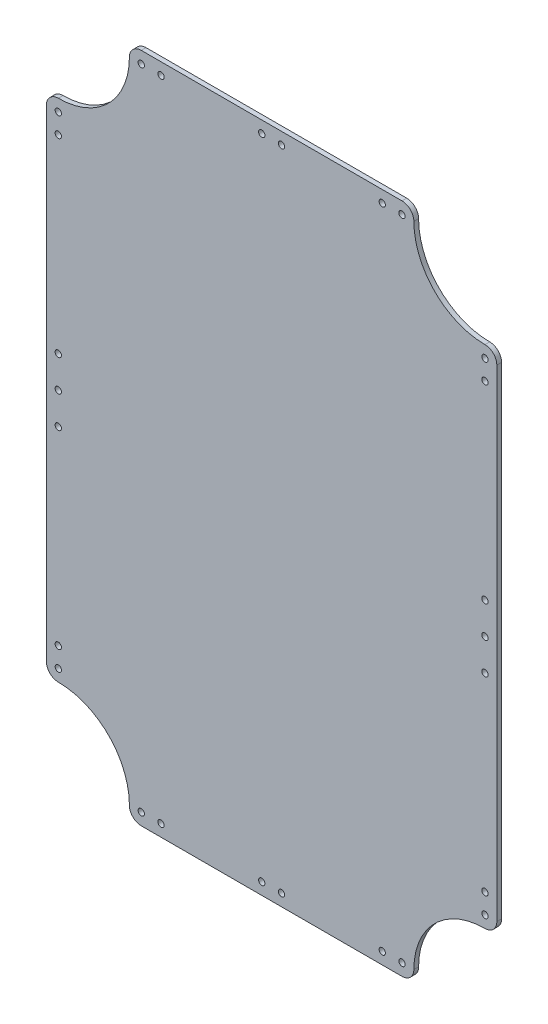
SolidWorks part; units mm, degrees
ref_plane "Front Plane" through (0, 0, 0) normal (0, 0, 1) x (1, 0, 0)
ref_plane "Top Plane" through (0, 0, 0) normal (0, 1, 0) x (1, 0, 0)
ref_plane "Right Plane" through (0, 0, 0) normal (1, 0, 0) x (0, 0, -1)
ref_plane "Plane1" through (0, 0, 0) normal (0, 0, -1) x (-1, 0, 0)
sketch "Sketch1" plane through (0, 0, 0) normal (0, 0, -1) x (-1, 0, 0)
  line L0 (-82.5, -212.5) -> (82.5, -212.5)
  line L1 (142.5, -152.5) -> (142.5, 152.5)
  line L2 (82.5, 212.5) -> (-82.5, 212.5)
  line L3 (-142.5, 152.5) -> (-142.5, -152.5)
  circle A0 centre (-135, 20) radius 2
  circle A1 centre (-135, -140) radius 2
  circle A2 centre (-82.5, -205) radius 2
  circle A3 centre (-6.25, -205) radius 2
  circle A4 centre (135, 20) radius 2
  circle A5 centre (135, 140) radius 2
  circle A6 centre (82.5, 205) radius 2
  circle A7 centre (70, 205) radius 2
  circle A8 centre (135, 152.5) radius 2
  circle A9 centre (135, 0) radius 2
  circle A10 centre (135, -20) radius 2
  circle A11 centre (-135, 0) radius 2
  circle A12 centre (135, -140) radius 2
  circle A13 centre (135, -152.5) radius 2
  circle A14 centre (82.5, -205) radius 2
  circle A15 centre (70, -205) radius 2
  circle A16 centre (6.25, -205) radius 2
  circle A17 centre (-70, -205) radius 2
  circle A18 centre (-135, -152.5) radius 2
  circle A19 centre (-135, -20) radius 2
  circle A22 centre (-135, 140) radius 2
  circle A23 centre (6.25, 205) radius 2
  circle A24 centre (-6.25, 205) radius 2
  circle A25 centre (-70, 205) radius 2
  circle A26 centre (-135, 152.5) radius 2
  circle A27 centre (-82.5, 205) radius 2
  arc A28 (-142.5, -152.5) -> (-135, -160) centre (-135, -152.5) ccw
  arc A29 (-135, -160) -> (-90, -205) centre (-135, -205) cw
  arc A30 (-90, -205) -> (-82.5, -212.5) centre (-82.5, -205) ccw
  arc A31 (82.5, -212.5) -> (90, -205) centre (82.5, -205) ccw
  arc A32 (90, -205) -> (135, -160) centre (135, -205) cw
  arc A33 (135, -160) -> (142.5, -152.5) centre (135, -152.5) ccw
  arc A34 (142.5, 152.5) -> (135, 160) centre (135, 152.5) ccw
  arc A35 (135, 160) -> (90, 205) centre (135, 205) cw
  arc A36 (90, 205) -> (82.5, 212.5) centre (82.5, 205) ccw
  arc A37 (-82.5, 212.5) -> (-90, 205) centre (-82.5, 205) ccw
  arc A38 (-90, 205) -> (-135, 160) centre (-135, 205) cw
  arc A39 (-135, 160) -> (-142.5, 152.5) centre (-135, 152.5) ccw
  dimension "D2" = 4
  dimension "D3" = 4
  dimension "D4" = 4
  dimension "D11" = 4
  dimension "D12" = 4
  dimension "D13" = 4
  dimension "D14" = 4
  dimension "D5" = 20
  dimension "D6" = 20
  dimension "D7" = 7.5
  dimension "D8" = 7.5
  dimension "D9" = 305
  dimension "D10" = 152.5
  dimension "D15" = 7.5
extrude "Boss-Extrude1" add sketch "Sketch1" against normal blind 3
